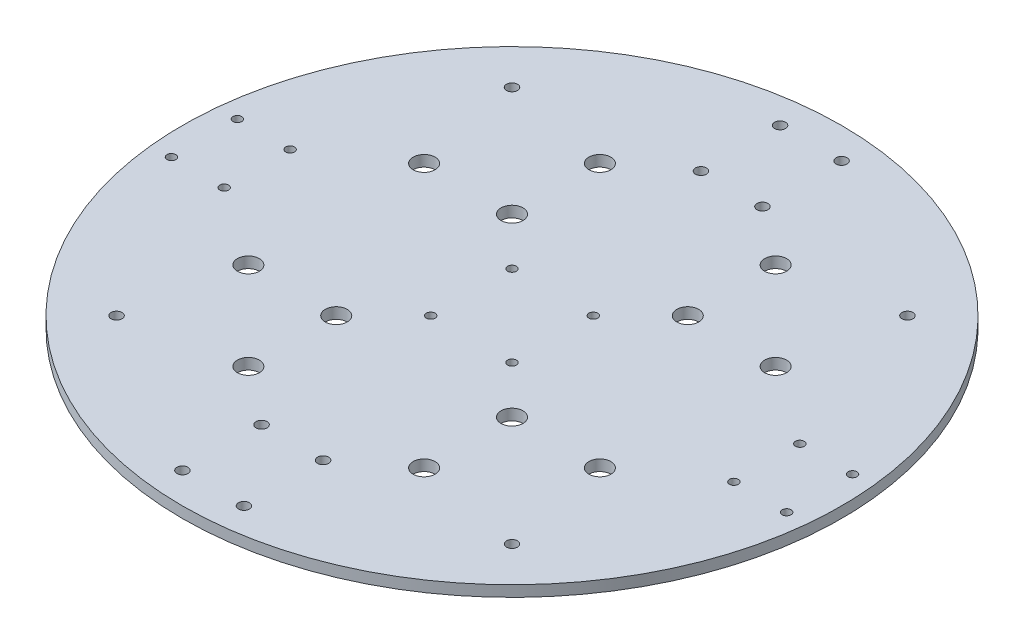
SolidWorks part; units mm, degrees
ref_plane "前视基准面" through (0, 0, 0) normal (0, 0, 1) x (1, 0, 0)
ref_plane "上视基准面" through (0, 0, 0) normal (0, 1, 0) x (1, 0, 0)
ref_plane "右视基准面" through (0, 0, 0) normal (1, 0, 0) x (0, 0, -1)
sketch "草图3" plane through (0, 0, 0) normal (0, 1, 0) x (1, 0, 0)
  circle A0 centre (0, 0) radius 150
  circle A1 centre (116, 15) radius 2
  circle A2 centre (140, 15) radius 2
  circle A3 centre (116, -15) radius 2
  circle A4 centre (140, -15) radius 2
  circle A5 centre (-140, -15) radius 2
  circle A6 centre (-140, 15) radius 2
  circle A7 centre (-116, 15) radius 2
  circle A8 centre (-116, -15) radius 2
  circle A9 centre (14, 100) radius 2.5
  circle A10 centre (-14, 100) radius 2.5
  circle A11 centre (14, 136) radius 2.5
  circle A12 centre (-14, 136) radius 2.5
  circle A13 centre (14, -100) radius 2.5
  circle A14 centre (14, -136) radius 2.5
  circle A15 centre (-14, -100) radius 2.5
  circle A16 centre (-14, -136) radius 2.5
  circle A17 centre (18.5, 18.5) radius 2
  circle A18 centre (-18.5, 18.5) radius 2
  circle A19 centre (-18.5, -18.5) radius 2
  circle A20 centre (18.5, -18.5) radius 2
  circle A21 centre (90, -90) radius 2.5
  circle A22 centre (90, 90) radius 2.5
  circle A23 centre (-90, 90) radius 2.5
  circle A24 centre (-90, -90) radius 2.5
  circle A25 centre (40, 40) radius 5
  circle A26 centre (40, -40) radius 5
  circle A27 centre (-40, 40) radius 5
  circle A28 centre (-40, -40) radius 5
  circle A29 centre (80, 40) radius 5
  circle A30 centre (80, -40) radius 5
  circle A31 centre (40, 80) radius 5
  circle A32 centre (-40, 80) radius 5
  circle A33 centre (-80, 40) radius 5
  circle A34 centre (-80, -40) radius 5
  circle A35 centre (-40, -80) radius 5
  circle A36 centre (40, -80) radius 5
extrude "凸台-拉伸2" add sketch "草图3" along normal blind 5
